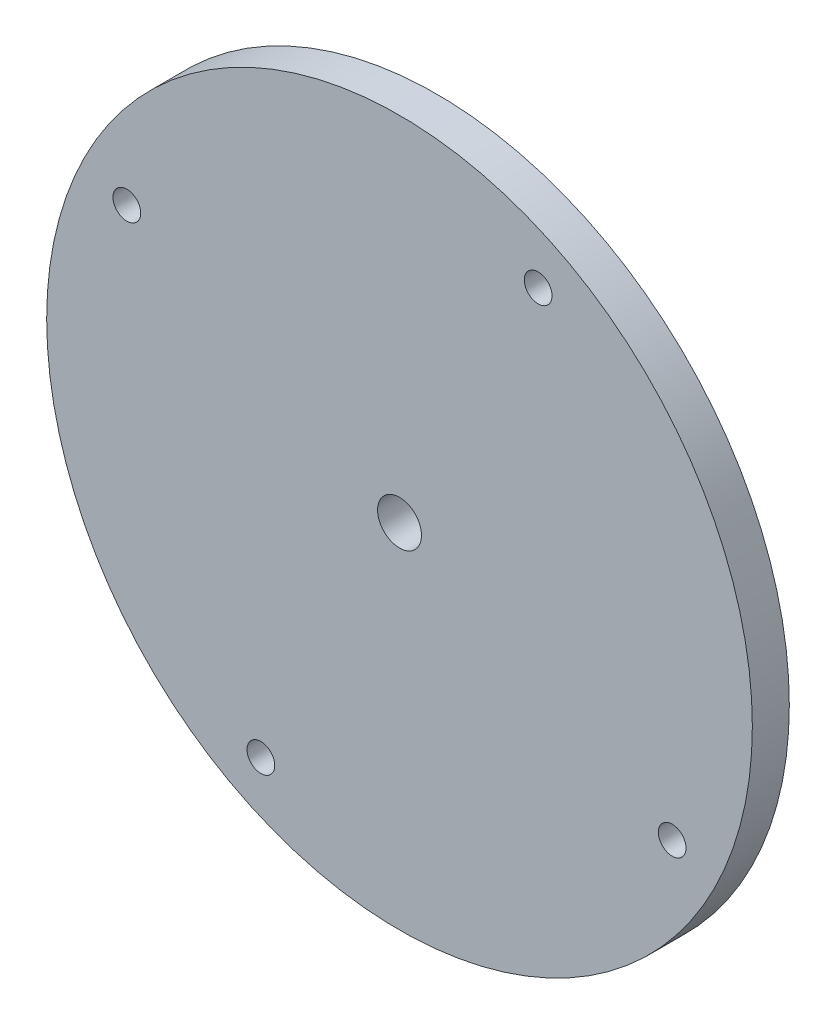
SolidWorks part; units mm, degrees
material "1060 Alloy"
ref_plane "Front Plane" through (0, 0, 0) normal (0, 0, 1) x (1, 0, 0)
ref_plane "Top Plane" through (0, 0, 0) normal (0, 1, 0) x (1, 0, 0)
ref_plane "Right Plane" through (0, 0, 0) normal (1, 0, 0) x (0, 0, -1)
sketch "Sketch1" plane through (0, 0, 0) normal (0, 0, 1) x (1, 0, 0)
  line L5 (50, -50) -> (-50, 50) construction
  line L6 (50, 50) -> (-50, -50) construction
  line L31 (24.5, 59) -> (27.25, 54.2369)
  line L32 (27.25, 54.2369) -> (32.75, 54.2369)
  line L33 (32.75, 54.2369) -> (35.5, 59)
  line L36 (-38.9, 50) -> (38.9, 50) construction
  line L50 (0, -76) -> (0, 122.6166) construction
  line L51 (-76, 0) -> (103.3867, 0) construction
  line L52 (35.5, 59) -> (32.75, 63.7631)
  line L53 (32.75, 63.7631) -> (27.25, 63.7631)
  line L54 (27.25, 63.7631) -> (24.5, 59)
  line L55 (-59, 24.5) -> (-54.2369, 27.25)
  line L56 (-54.2369, 27.25) -> (-54.2369, 32.75)
  line L57 (-54.2369, 32.75) -> (-59, 35.5)
  line L58 (-59, 35.5) -> (-63.7631, 32.75)
  line L59 (-63.7631, 32.75) -> (-63.7631, 27.25)
  line L60 (-63.7631, 27.25) -> (-59, 24.5)
  line L61 (59, -24.5) -> (54.2369, -27.25)
  line L62 (54.2369, -27.25) -> (54.2369, -32.75)
  line L96 (54.2369, -32.75) -> (59, -35.5)
  line L97 (59, -35.5) -> (63.7631, -32.75)
  line L98 (63.7631, -32.75) -> (63.7631, -27.25)
  line L99 (63.7631, -27.25) -> (59, -24.5)
  line L100 (-24.5, -59) -> (-27.25, -54.2369)
  line L101 (-27.25, -54.2369) -> (-32.75, -54.2369)
  line L102 (-32.75, -54.2369) -> (-35.5, -59)
  line L103 (-35.5, -59) -> (-32.75, -63.7631)
  line L104 (-32.75, -63.7631) -> (-27.25, -63.7631)
  line L105 (-27.25, -63.7631) -> (-24.5, -59)
  arc A0 (0, 76.35) -> (-72.3486, -24.3928) centre (0, 0) ccw
  circle A1 centre (30, 59) radius 3
  arc A2 (76.35, 0) -> (0, 76.35) centre (0, 0) ccw
  arc A3 (-72.3486, -24.3928) -> (0, -76.35) centre (0, 0) ccw
  arc A4 (0, -76.35) -> (76.35, 0) centre (0, 0) ccw
  circle A5 centre (59, -30) radius 3
  circle A6 centre (-30, -59) radius 3
  circle A7 centre (-59, 30) radius 3
  circle A8 centre (30, 59) radius 5.5 construction
  circle A9 centre (-59, 30) radius 5.5 construction
  circle A10 centre (59, -30) radius 5.5 construction
  circle A11 centre (-30, -59) radius 5.5 construction
  dimension "D1" = 152.7
  dimension "D9" = 30
  dimension "D2" = 59
  dimension "D15" = 11
  dimension "D16" = 11
  dimension "D17" = 11
  dimension "D3" = 30
  dimension "D4" = 59
  dimension "D5" = 59
  dimension "D6" = 59
  dimension "D10" = 30
  dimension "D11" = 30
extrude "Boss-Extrude3" add sketch "Sketch1" along normal blind 8
sketch "Sketch2" plane through (0, 0, 8) normal (0, 0, 1) x (1, 0, 0)
  circle A0 centre (0, 0) radius 4.75
  dimension "D1" = 9.5
extrude "Cut-Extrude1" cut sketch "Sketch2" against normal through all
